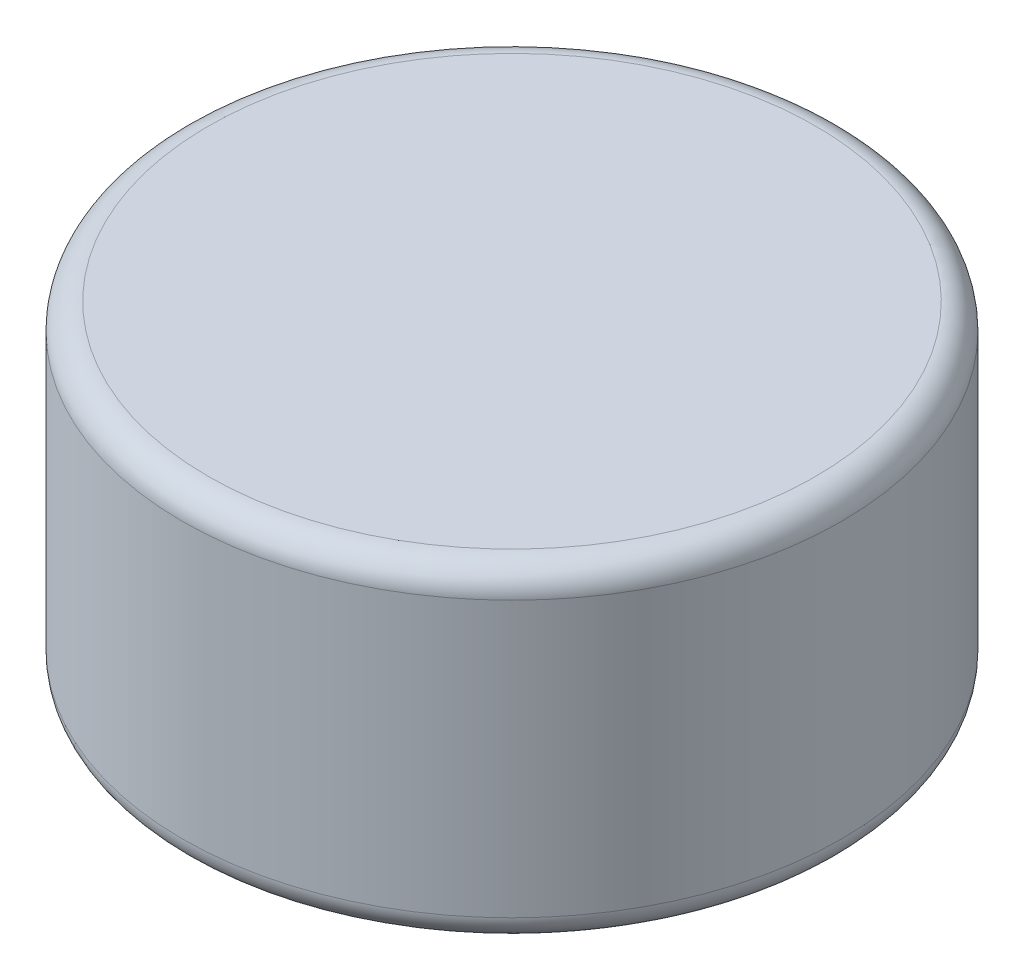
SolidWorks part; units mm, degrees
ref_plane "Front Plane" through (0, 0, 0) normal (0, 0, 1) x (1, 0, 0)
ref_plane "Top Plane" through (0, 0, 0) normal (0, 1, 0) x (1, 0, 0)
ref_plane "Right Plane" through (0, 0, 0) normal (1, 0, 0) x (0, 0, -1)
sketch "Sketch1" plane through (0, 0, 0) normal (0, 1, 0) x (1, 0, 0)
  circle A0 centre (0, 0) radius 6.35
  dimension "D1" = 12.7
extrude "Boss-Extrude1" add sketch "Sketch1" along normal blind 6.3
fillet "Fillet1" radius 0.5 2 edges at (0, 0, 6.35) (0, 6.3, 6.35)
